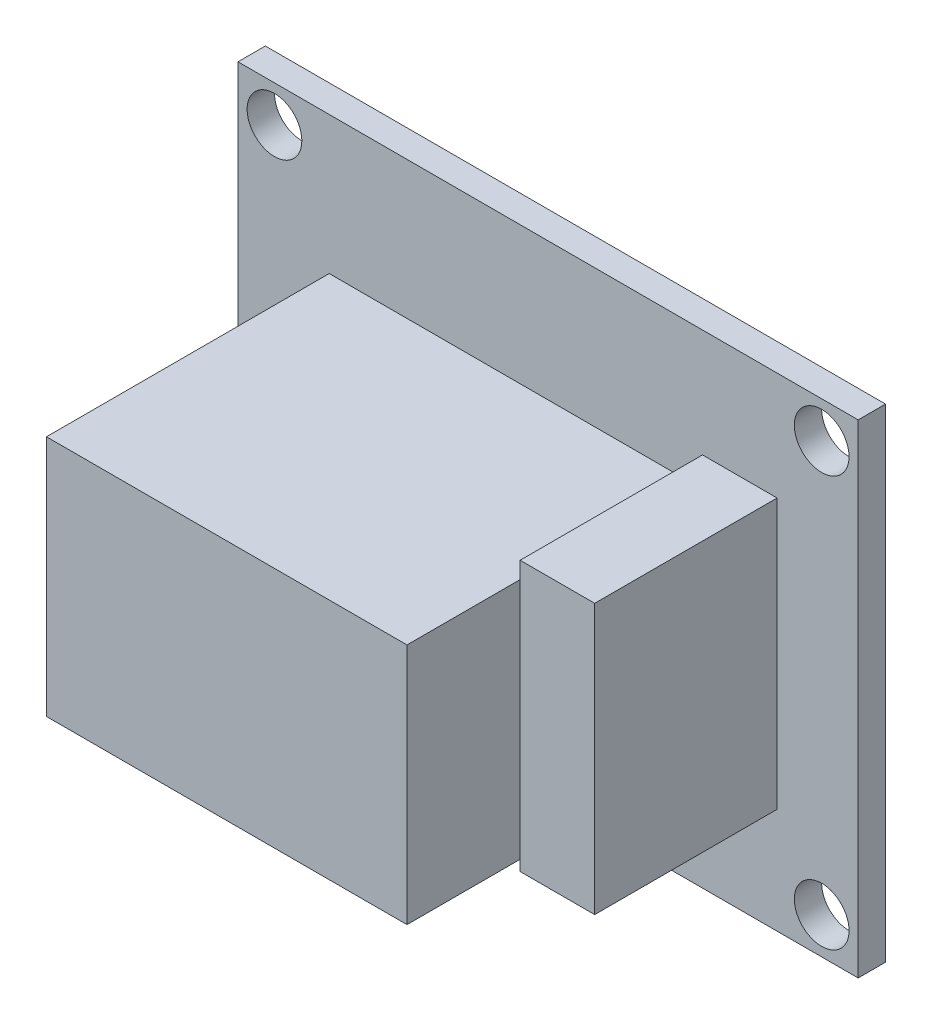
SolidWorks part; units mm, degrees
ref_plane "Front Plane" through (0, 0, 0) normal (0, 0, 1) x (1, 0, 0)
ref_plane "Top Plane" through (0, 0, 0) normal (0, 1, 0) x (1, 0, 0)
ref_plane "Right Plane" through (0, 0, 0) normal (1, 0, 0) x (0, 0, -1)
sketch "Sketch1" plane through (0, 0, 0) normal (0, 0, 1) x (1, 0, 0)
  line L0 (2, 24.5) -> (32, 24.5) construction
  line L1 (0, 0) -> (34, 0)
  line L2 (0, 0) -> (0, 26.5)
  line L3 (0, 26.5) -> (34, 26.5)
  line L4 (34, 0) -> (34, 26.5)
  line L5 (32, 2) -> (32, 24.5) construction
  line L6 (2, 2) -> (32, 2) construction
  line L7 (2, 2) -> (2, 24.5) construction
  circle A0 centre (2, 24.5) radius 1.5
  circle A1 centre (32, 24.5) radius 1.5
  circle A2 centre (2, 2) radius 1.5
  circle A3 centre (32, 2) radius 1.5
  dimension "D1" = 34
  dimension "D2" = 26.5
  dimension "D3" = 2
extrude "Boss-Extrude1" add sketch "Sketch1" along normal blind 1.5
sketch "Sketch2" plane through (0, 0, 1.5) normal (0, 0, 1) x (1, 0, 0)
  line L1 (5.0008, 18.9472) -> (24.7656, 18.9472)
  line L2 (5.0008, 18.9472) -> (5.0008, 5.6658)
  line L3 (5.0008, 5.6658) -> (24.7656, 5.6658)
  line L4 (24.7656, 18.9472) -> (24.7656, 5.6658)
extrude "Boss-Extrude2" add sketch "Sketch2" along normal blind 15.5
sketch "Sketch3" plane through (0, 0, 1.5) normal (0, 0, 1) x (1, 0, 0)
  line L1 (25.4672, 20.5681) -> (29.5556, 20.5681)
  line L2 (25.4672, 20.5681) -> (25.4672, 5.7868)
  line L3 (25.4672, 5.7868) -> (29.5556, 5.7868)
  line L4 (29.5556, 20.5681) -> (29.5556, 5.7868)
extrude "Boss-Extrude3" add sketch "Sketch3" along normal blind 10
